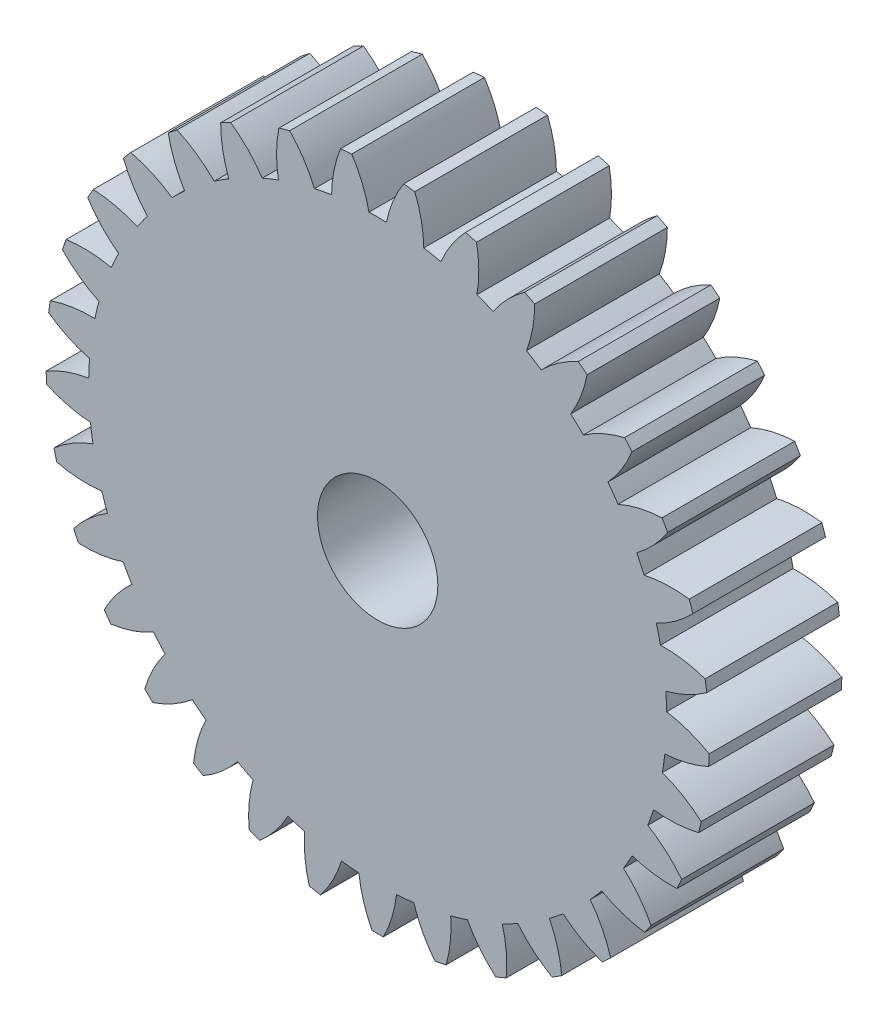
SolidWorks part; units mm, degrees
ref_plane "Alzado" through (0, 0, 0) normal (0, 0, 1) x (1, 0, 0)
ref_plane "Planta" through (0, 0, 0) normal (0, 1, 0) x (1, 0, 0)
ref_plane "Vista lateral" through (0, 0, 0) normal (1, 0, 0) x (0, 0, -1)
sketch "Croquis1" plane through (0, 0, 0) normal (0, 0, 1) x (1, 0, 0)
  line L0 (13.6206, 0) -> (-13.971, 0) construction
  line L1 (-0.46, 15.2421) -> (0, 0) construction
  line L2 (0.46, 15.2421) -> (0, 0) construction
  line L3 (1.3662, 17.4466) -> (0, 0) construction
  line L4 (1.9603, 17.3899) -> (0, 0) construction
  line L5 (0, -3.6901) -> (0, 21.5552) construction
  circle A0 centre (0, 0) radius 3.175
  arc A29 (2.4329, 15.0537) -> (1.9603, 17.3899) centre (-4.1661, 14.9347) ccw
  arc A30 (1.9603, 17.3899) -> (1.3662, 17.4466) centre (0, 0) ccw
  arc A31 (1.3662, 17.4466) -> (0.46, 15.2421) centre (6.9172, 13.8764) ccw
  arc A32 (0.46, 15.2421) -> (-0.46, 15.2421) centre (0, 0) ccw
  circle A133 centre (0, 0) radius 15.249 construction
  circle A134 centre (0, 0) radius 17.5 construction
  arc A135 (3.3363, 14.8796) -> (2.4329, 15.0537) centre (0, 0) ccw
  arc A136 (4.6433, 16.8728) -> (3.3363, 14.8796) centre (9.4183, 12.3166) ccw
  arc A137 (5.2159, 16.7046) -> (4.6433, 16.8728) centre (0, 0) ccw
  arc A138 (5.2378, 14.3212) -> (5.2159, 16.7046) centre (-1.2644, 15.4533) ccw
  arc A139 (6.092, 13.9793) -> (5.2378, 14.3212) centre (0, 0) ccw
  arc A140 (7.7526, 15.6891) -> (6.092, 13.9793) centre (11.5791, 10.3116) ccw
  arc A141 (8.283, 15.4156) -> (7.7526, 15.6891) centre (0, 0) ccw
  arc A142 (7.8535, 13.0712) -> (8.283, 15.4156) centre (1.683, 15.4133) ccw
  arc A143 (8.6275, 12.5737) -> (7.8535, 13.0712) centre (0, 0) ccw
  arc A144 (10.5816, 13.9384) -> (8.6275, 12.5737) centre (13.3213, 7.9339) ccw
  arc A145 (11.0508, 13.5695) -> (10.5816, 13.9384) centre (0, 0) ccw
  arc A146 (10.1853, 11.3487) -> (11.0508, 13.5695) centre (4.5696, 14.8163) ccw
  arc A147 (10.8512, 10.7137) -> (10.1853, 11.3487) centre (0, 0) ccw
  arc A148 (13.0283, 11.6839) -> (10.8512, 10.7137) centre (14.582, 5.2694) ccw
  arc A149 (13.4191, 11.2329) -> (13.0283, 11.6839) centre (0, 0) ccw
  arc A150 (12.149, 9.216) -> (13.4191, 11.2329) centre (7.291, 13.6837) ccw
  arc A151 (12.6827, 8.4665) -> (12.149, 9.216) centre (0, 0) ccw
  arc A152 (15.004, 9.0072) -> (12.6827, 8.4665) centre (15.3158, 2.4145) ccw
  arc A153 (15.3024, 8.4903) -> (15.004, 9.0072) centre (0, 0) ccw
  arc A154 (13.6736, 6.7502) -> (15.3024, 8.4903) centre (9.7489, 12.0566) ccw
  arc A155 (14.0558, 5.9133) -> (13.6736, 6.7502) centre (0, 0) ccw
  arc A156 (16.4375, 6.0049) -> (14.0558, 5.9133) centre (15.4959, -0.5276) ccw
  arc A157 (16.6327, 5.4409) -> (16.4375, 6.0049) centre (0, 0) ccw
  arc A158 (14.704, 4.0405) -> (16.6327, 5.4409) centre (11.8545, 9.9937) ccw
  arc A159 (14.9209, 3.1464) -> (14.704, 4.0405) centre (0, 0) ccw
  arc A160 (17.2769, 2.7855) -> (14.9209, 3.1464) centre (15.1161, -3.4507) ccw
  arc A161 (17.3618, 2.1948) -> (17.2769, 2.7855) centre (0, 0) ccw
  arc A162 (15.2029, 1.1848) -> (17.3618, 2.1948) centre (13.5316, 7.5696) ccw
  arc A163 (15.2467, 0.2657) -> (15.2029, 1.1848) centre (0, 0) ccw
  arc A164 (17.4918, -0.5345) -> (15.2467, 0.2657) centre (14.1898, -6.2491) ccw
  arc A165 (17.4634, -1.1306) -> (17.4918, -0.5345) centre (0, 0) ccw
  arc A166 (15.1524, -1.7138) -> (17.4634, -1.1306) centre (14.7196, 4.872) ccw
  arc A167 (15.0214, -2.6245) -> (15.1524, -1.7138) centre (0, 0) ccw
  arc A168 (17.0746, -3.8352) -> (15.0214, -2.6245) centre (12.7508, -8.8216) ccw
  arc A169 (16.9339, -4.4152) -> (17.0746, -3.8352) centre (0, 0) ccw
  arc A170 (14.5542, -4.5505) -> (16.9339, -4.4152) centre (15.3756, 1.9982) ccw
  arc A171 (14.2533, -5.4199) -> (14.5542, -4.5505) centre (0, 0) ccw
  arc A172 (16.0402, -6.9973) -> (14.2533, -5.4199) centre (10.8508, -11.0753) ccw
  arc A173 (15.7923, -7.5401) -> (16.0402, -6.9973) centre (0, 0) ccw
  arc A174 (13.43, -7.2226) -> (15.7923, -7.5401) centre (15.4759, -0.9477) ccw
  arc A175 (12.97, -8.0194) -> (13.43, -7.2226) centre (0, 0) ccw
  arc A176 (14.4261, -9.9064) -> (12.97, -8.0194) centre (8.5587, -12.9287) ccw
  arc A177 (14.0799, -10.3926) -> (14.4261, -9.9064) centre (0, 0) ccw
  arc A178 (11.8204, -9.6338) -> (14.0799, -10.3926) centre (15.0169, -3.8594) ccw
  arc A179 (11.2179, -10.3291) -> (11.8204, -9.6338) centre (0, 0) ccw
  arc A180 (12.2906, -12.4576) -> (11.2179, -10.3291) centre (5.9573, -14.3148) ccw
  arc A181 (11.8587, -12.8694) -> (12.2906, -12.4576) centre (0, 0) ccw
  arc A182 (9.7836, -11.6967) -> (11.8587, -12.8694) centre (14.0151, -6.6317) ccw
  arc A183 (9.0604, -12.2654) -> (9.7836, -11.6967) centre (0, 0) ccw
  arc A184 (9.7109, -14.5585) -> (9.0604, -12.2654) centre (3.1405, -15.1835) ccw
  arc A185 (9.2088, -14.8811) -> (9.7109, -14.5585) centre (0, 0) ccw
  arc A186 (7.3932, -13.3369) -> (9.2088, -14.8811) centre (12.5068, -9.1642) ccw
  arc A187 (6.5754, -13.7585) -> (7.3932, -13.3369) centre (0, 0) ccw
  arc A188 (6.7802, -16.1332) -> (6.5754, -13.7585) centre (0.2103, -15.5035) ccw
  arc A189 (6.2261, -16.355) -> (6.7802, -16.1332) centre (0, 0) ccw
  arc A190 (4.7356, -14.495) -> (6.2261, -16.355) centre (10.5465, -11.3655) ccw
  arc A191 (3.8528, -14.7543) -> (4.7356, -14.495) centre (0, 0) ccw
  arc A192 (3.6044, -17.1248) -> (3.8528, -14.7543) centre (-2.7276, -15.2631) ccw
  arc A193 (3.0184, -17.2377) -> (3.6044, -17.1248) centre (0, 0) ccw
  arc A194 (1.9068, -15.1293) -> (3.0184, -17.2377) centre (8.2049, -13.1561) ccw
  arc A195 (0.9909, -15.2168) -> (1.9068, -15.1293) centre (0, 0) ccw
  arc A196 (0.2984, -17.4975) -> (0.9909, -15.2168) centre (-5.5668, -14.4711) ccw
  arc A197 (-0.2984, -17.4975) -> (0.2984, -17.4975) centre (0, 0) ccw
  arc A198 (-0.9909, -15.2168) -> (-0.2984, -17.4975) centre (5.5668, -14.4711) ccw
  arc A199 (-1.9068, -15.1293) -> (-0.9909, -15.2168) centre (0, 0) ccw
  arc A200 (-3.0184, -17.2377) -> (-1.9068, -15.1293) centre (-8.2049, -13.1561) ccw
  arc A201 (-3.6044, -17.1248) -> (-3.0184, -17.2377) centre (0, 0) ccw
  arc A202 (-3.8528, -14.7543) -> (-3.6044, -17.1248) centre (2.7276, -15.2631) ccw
  arc A203 (-4.7356, -14.495) -> (-3.8528, -14.7543) centre (0, 0) ccw
  arc A204 (-6.2261, -16.355) -> (-4.7356, -14.495) centre (-10.5465, -11.3655) ccw
  arc A205 (-6.7802, -16.1332) -> (-6.2261, -16.355) centre (0, 0) ccw
  arc A206 (-6.5754, -13.7585) -> (-6.7802, -16.1332) centre (-0.2103, -15.5035) ccw
  arc A207 (-7.3932, -13.3369) -> (-6.5754, -13.7585) centre (0, 0) ccw
  arc A208 (-9.2088, -14.8811) -> (-7.3932, -13.3369) centre (-12.5068, -9.1642) ccw
  arc A209 (-9.7109, -14.5585) -> (-9.2088, -14.8811) centre (0, 0) ccw
  arc A210 (-9.0604, -12.2654) -> (-9.7109, -14.5585) centre (-3.1405, -15.1835) ccw
  arc A211 (-9.7836, -11.6967) -> (-9.0604, -12.2654) centre (0, 0) ccw
  arc A212 (-11.8587, -12.8694) -> (-9.7836, -11.6967) centre (-14.0151, -6.6317) ccw
  arc A213 (-12.2906, -12.4576) -> (-11.8587, -12.8694) centre (0, 0) ccw
  arc A214 (-11.2179, -10.3291) -> (-12.2906, -12.4576) centre (-5.9573, -14.3148) ccw
  arc A215 (-11.8204, -9.6338) -> (-11.2179, -10.3291) centre (0, 0) ccw
  arc A216 (-14.0799, -10.3926) -> (-11.8204, -9.6338) centre (-15.0169, -3.8594) ccw
  arc A217 (-14.4261, -9.9064) -> (-14.0799, -10.3926) centre (0, 0) ccw
  arc A218 (-12.97, -8.0194) -> (-14.4261, -9.9064) centre (-8.5587, -12.9287) ccw
  arc A219 (-13.43, -7.2226) -> (-12.97, -8.0194) centre (0, 0) ccw
  arc A220 (-15.7923, -7.5401) -> (-13.43, -7.2226) centre (-15.4759, -0.9477) ccw
  arc A221 (-16.0402, -6.9973) -> (-15.7923, -7.5401) centre (0, 0) ccw
  arc A222 (-14.2533, -5.4199) -> (-16.0402, -6.9973) centre (-10.8508, -11.0753) ccw
  arc A223 (-14.5542, -4.5505) -> (-14.2533, -5.4199) centre (0, 0) ccw
  arc A224 (-16.9339, -4.4152) -> (-14.5542, -4.5505) centre (-15.3756, 1.9982) ccw
  arc A225 (-17.0746, -3.8352) -> (-16.9339, -4.4152) centre (0, 0) ccw
  arc A226 (-15.0214, -2.6245) -> (-17.0746, -3.8352) centre (-12.7508, -8.8216) ccw
  arc A227 (-15.1524, -1.7138) -> (-15.0214, -2.6245) centre (0, 0) ccw
  arc A228 (-17.4634, -1.1306) -> (-15.1524, -1.7138) centre (-14.7196, 4.872) ccw
  arc A229 (-17.4918, -0.5345) -> (-17.4634, -1.1306) centre (0, 0) ccw
  arc A230 (-15.2467, 0.2657) -> (-17.4918, -0.5345) centre (-14.1898, -6.2491) ccw
  arc A231 (-15.2029, 1.1848) -> (-15.2467, 0.2657) centre (0, 0) ccw
  arc A232 (-17.3618, 2.1948) -> (-15.2029, 1.1848) centre (-13.5316, 7.5696) ccw
  arc A233 (-17.2769, 2.7855) -> (-17.3618, 2.1948) centre (0, 0) ccw
  arc A234 (-14.9209, 3.1464) -> (-17.2769, 2.7855) centre (-15.1161, -3.4507) ccw
  arc A235 (-14.704, 4.0405) -> (-14.9209, 3.1464) centre (0, 0) ccw
  arc A236 (-16.6327, 5.4409) -> (-14.704, 4.0405) centre (-11.8545, 9.9937) ccw
  arc A237 (-16.4375, 6.0049) -> (-16.6327, 5.4409) centre (0, 0) ccw
  arc A238 (-14.0558, 5.9133) -> (-16.4375, 6.0049) centre (-15.4959, -0.5276) ccw
  arc A239 (-13.6736, 6.7502) -> (-14.0558, 5.9133) centre (0, 0) ccw
  arc A240 (-15.3024, 8.4903) -> (-13.6736, 6.7502) centre (-9.7489, 12.0566) ccw
  arc A241 (-15.004, 9.0072) -> (-15.3024, 8.4903) centre (0, 0) ccw
  arc A242 (-12.6827, 8.4665) -> (-15.004, 9.0072) centre (-15.3158, 2.4145) ccw
  arc A243 (-12.149, 9.216) -> (-12.6827, 8.4665) centre (0, 0) ccw
  arc A244 (-13.4191, 11.2329) -> (-12.149, 9.216) centre (-7.291, 13.6837) ccw
  arc A245 (-13.0283, 11.6839) -> (-13.4191, 11.2329) centre (0, 0) ccw
  arc A246 (-10.8512, 10.7137) -> (-13.0283, 11.6839) centre (-14.582, 5.2694) ccw
  arc A247 (-10.1853, 11.3487) -> (-10.8512, 10.7137) centre (0, 0) ccw
  arc A248 (-11.0508, 13.5695) -> (-10.1853, 11.3487) centre (-4.5696, 14.8163) ccw
  arc A249 (-10.5816, 13.9384) -> (-11.0508, 13.5695) centre (0, 0) ccw
  arc A250 (-8.6275, 12.5737) -> (-10.5816, 13.9384) centre (-13.3213, 7.9339) ccw
  arc A251 (-7.8535, 13.0712) -> (-8.6275, 12.5737) centre (0, 0) ccw
  arc A252 (-8.283, 15.4156) -> (-7.8535, 13.0712) centre (-1.683, 15.4133) ccw
  arc A253 (-7.7526, 15.6891) -> (-8.283, 15.4156) centre (0, 0) ccw
  arc A254 (-6.092, 13.9793) -> (-7.7526, 15.6891) centre (-11.5791, 10.3116) ccw
  arc A255 (-5.2378, 14.3212) -> (-6.092, 13.9793) centre (0, 0) ccw
  arc A256 (-5.2159, 16.7046) -> (-5.2378, 14.3212) centre (1.2644, 15.4533) ccw
  arc A257 (-4.6433, 16.8728) -> (-5.2159, 16.7046) centre (0, 0) ccw
  arc A258 (-3.3363, 14.8796) -> (-4.6433, 16.8728) centre (-9.4183, 12.3166) ccw
  arc A259 (-2.4329, 15.0537) -> (-3.3363, 14.8796) centre (0, 0) ccw
  arc A260 (-1.9603, 17.3899) -> (-2.4329, 15.0537) centre (4.1661, 14.9347) ccw
  arc A261 (-1.3662, 17.4466) -> (-1.9603, 17.3899) centre (0, 0) ccw
  arc A262 (-0.46, 15.2421) -> (-1.3662, 17.4466) centre (-6.9172, 13.8764) ccw
  point P244 (0, 0)
  dimension "D1" = 6.35
  dimension "D2" = 88.271
  dimension "D3" = 35
  dimension "D8" = 6.9172
  dimension "D11" = 30.498
  dimension "D4" = 91.729
  dimension "D5" = 94.477
  dimension "D6" = 96.432
  dimension "D7" = 13.8764
  dimension "D9" = 4.1661
  dimension "D10" = 14.9347
  dimension "D12" = 33
extrude "Saliente-Extruir1" add sketch "Croquis1" along normal blind 7
